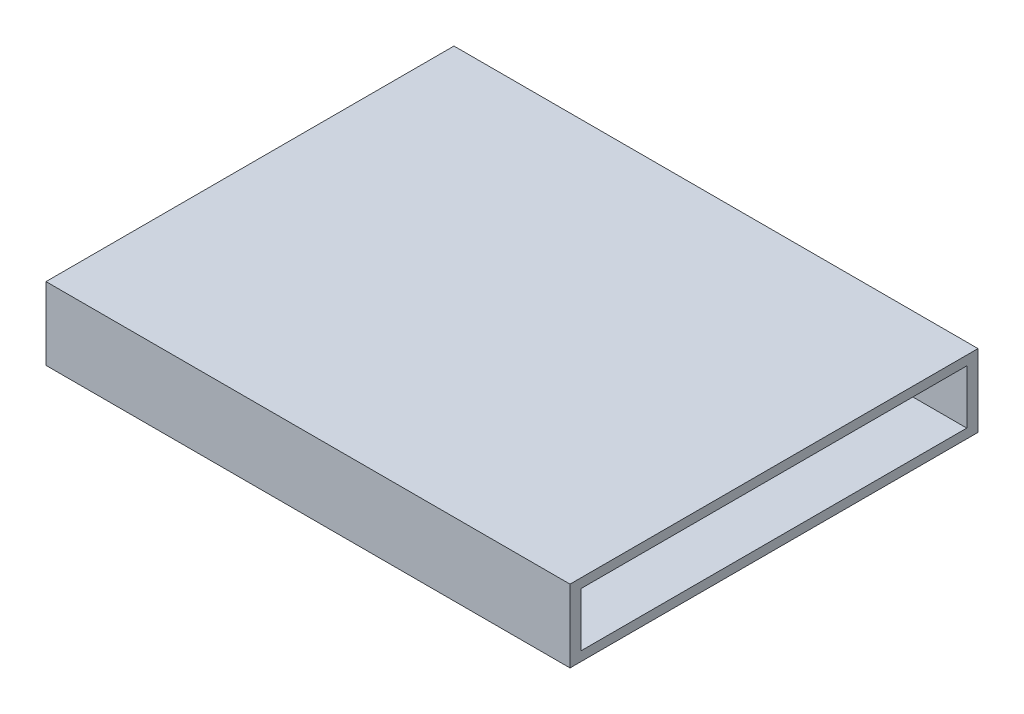
SolidWorks part; units mm, degrees
ref_plane "Front Plane" through (0, 0, 0) normal (0, 0, 1) x (1, 0, 0)
ref_plane "Top Plane" through (0, 0, 0) normal (0, 1, 0) x (1, 0, 0)
ref_plane "Right Plane" through (0, 0, 0) normal (1, 0, 0) x (0, 0, -1)
sketch "Sketch2" plane through (0, 0, 0) normal (0, 1, 0) x (1, 0, 0)
  line L1 (0, 0) -> (17.78, 0)
  line L2 (0, 0) -> (0, 13.843)
  line L3 (0, 13.843) -> (17.78, 13.843)
  line L4 (17.78, 0) -> (17.78, 13.843)
  dimension "D1" = 17.78
  dimension "D2" = 13.843
extrude "Boss-Extrude1" add sketch "Sketch2" along normal blind 2.4638
sketch "Sketch3" plane through (17.78, 0, 0) normal (1, 0, 0) x (0, 0, -1)
  line L0 (6.9215, 2.1463) -> (6.9215, 0.3175) construction
  line L1 (0.381, 0.3175) -> (13.462, 0.3175)
  line L2 (0.381, 0.3175) -> (0.381, 2.1463)
  line L3 (0.381, 2.1463) -> (13.462, 2.1463)
  line L4 (13.462, 0.3175) -> (13.462, 2.1463)
  line L5 (6.9215, 2.4638) -> (6.9215, 0) construction
  line L6 (0, 2.4638) -> (13.843, 2.4638) construction
  line L7 (0, 0) -> (13.843, 0) construction
  dimension "D1" = 13.081
  dimension "D2" = 0.3175
  dimension "D3" = 0.3175
extrude "Cut-Extrude1" cut sketch "Sketch3" against normal blind 17.3736
